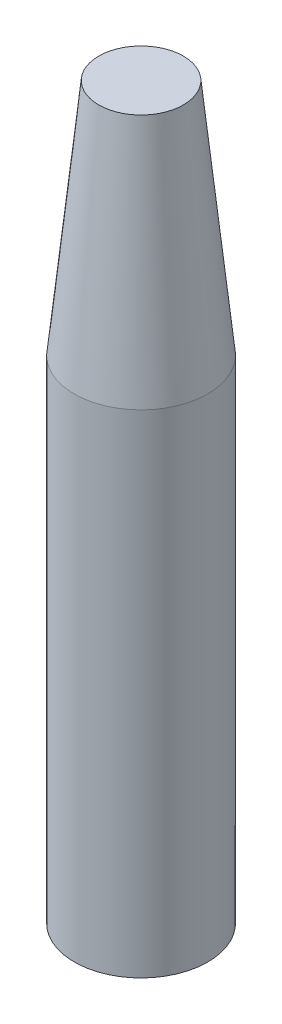
SolidWorks part; units mm, degrees
ref_plane "Front Plane" through (0, 0, 0) normal (0, 0, 1) x (1, 0, 0)
ref_plane "Top Plane" through (0, 0, 0) normal (0, 1, 0) x (1, 0, 0)
ref_plane "Right Plane" through (0, 0, 0) normal (1, 0, 0) x (0, 0, -1)
sketch "Sketch1" plane through (0, 0, 0) normal (0, 1, 0) x (1, 0, 0)
  circle A0 centre (0, 0) radius 12.625
  dimension "D1" = 25.25
extrude "Boss-Extrude1" add sketch "Sketch1" along normal blind 93
sketch "Sketch2" plane through (0, 93, 0) normal (0, 1, 0) x (1, 0, 0)
  circle A0 centre (0, 0) radius 8
  dimension "D1" = 16
extrude "Boss-Extrude2" add sketch "Sketch2" along normal blind 45
sketch "Sketch3" plane through (0, 0, 0) normal (0, 0, 1) x (1, 0, 0)
  line L0 (8, 138) -> (-8, 138) construction
  line L1 (8, 93) -> (8, 138) construction
  line L2 (12.625, 93) -> (-12.625, 93) construction
  line L3 (8, 138) -> (-8, 138)
  line L4 (8, 93) -> (8, 138)
  line L5 (12.625, 93) -> (-12.625, 93)
  line L6 (8, 138) -> (12.625, 93)
  line L7 (8, 93) -> (8, 138)
  line L8 (0, 138) -> (0, 93)
revolve "Revolve1" add sketch "Sketch3" angle 360 about L8
equation "\"D1@Sketch1\"=25.25mm"
